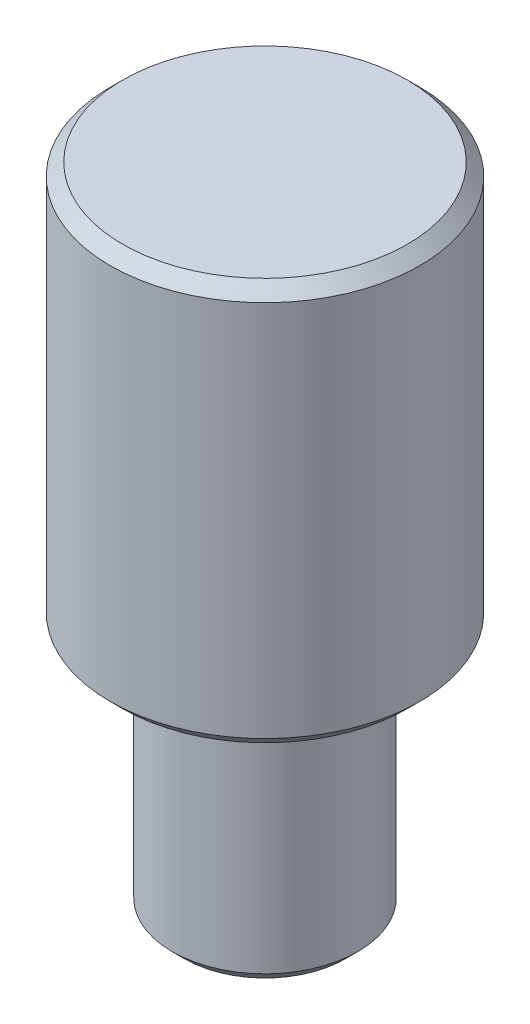
SolidWorks part; units mm, degrees
material "Plain Carbon Steel"
ref_plane "Front Plane" through (0, 0, 0) normal (0, 0, 1) x (1, 0, 0)
ref_plane "Top Plane" through (0, 0, 0) normal (0, 1, 0) x (1, 0, 0)
ref_plane "Right Plane" through (0, 0, 0) normal (1, 0, 0) x (0, 0, -1)
sketch "Sketch1" plane through (0, 0, 0) normal (0, 0, 1) x (1, 0, 0)
  line L0 (0, 0) -> (0, -100) construction
  line L1 (0, 0) -> (25, 0)
  line L2 (25, 0) -> (25, -65)
  line L3 (25, -65) -> (15, -65)
  line L4 (15, -65) -> (15, -105)
  line L5 (15, -105) -> (0, -105)
  line L6 (0, -105) -> (0, 0)
  dimension "D1" = 100
  dimension "D2" = 30
  dimension "D3" = 50
  dimension "D4" = 65
  dimension "D5" = 40
revolve "Revolve1" add sketch "Sketch1" angle 360 about L0
chamfer "Chamfer1" distance 2 angle 45 1 edges at (0, -105, 15)
cosmetic thread "Cosmetic Thread1" parameters "D2"=26.158
chamfer "Chamfer2" distance 2 angle 45 2 edges at (0, -65, 25) (0, 0, 25)
